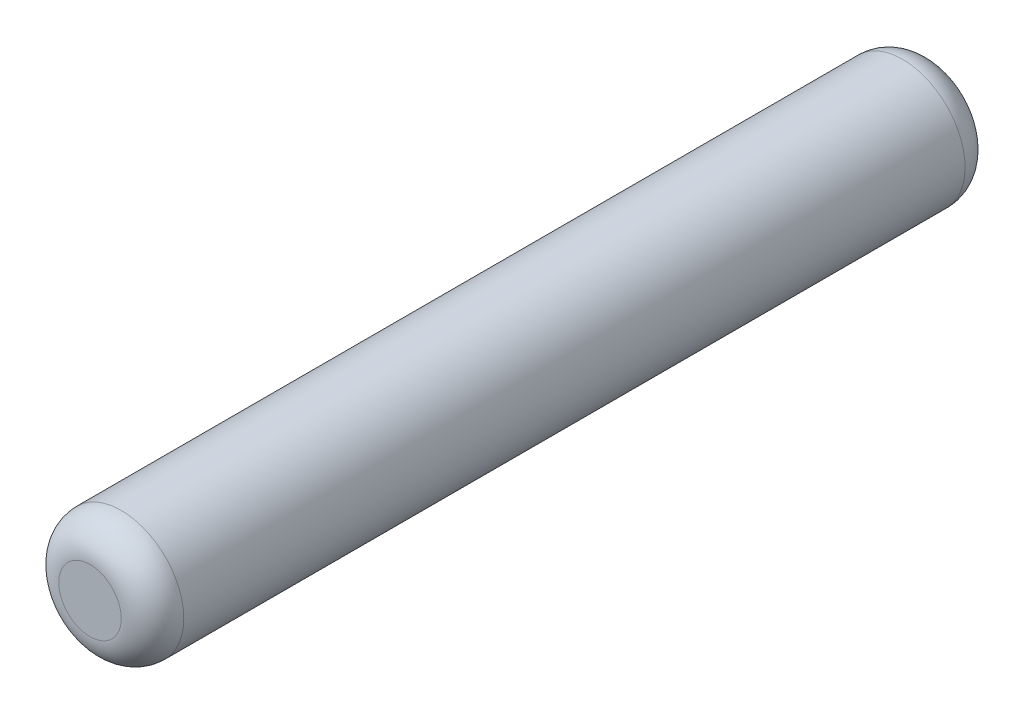
SolidWorks part; units mm, degrees
ref_plane "Plan1" through (0, 0, 0) normal (0, 0, 1) x (1, 0, 0)
ref_plane "Plan2" through (0, 0, 0) normal (0, 1, 0) x (1, 0, 0)
ref_plane "Plan3" through (0, 0, 0) normal (1, 0, 0) x (0, 0, -1)
sketch "Esquisse1" plane through (0, 0, 0) normal (0, 0, 1) x (1, 0, 0)
  circle A0 centre (0, 0) radius 2
  dimension "D1" = 4
extrude "Base-Extrusion" add sketch "Esquisse1" along normal blind 27
fillet "Congé1" radius 1
